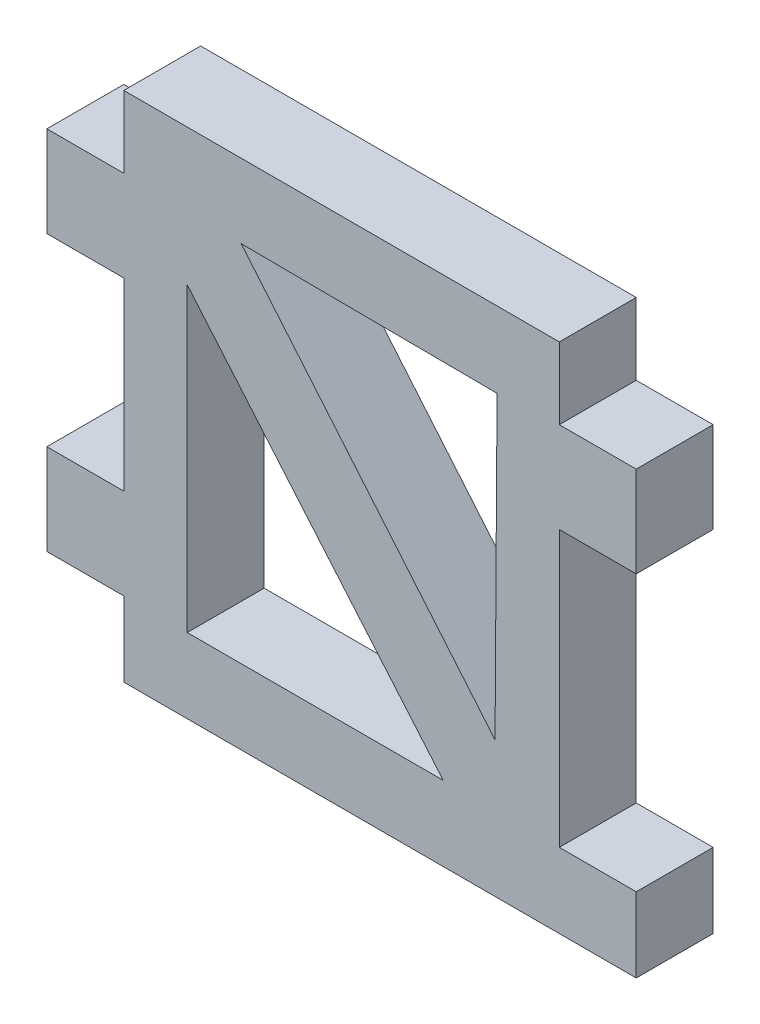
SolidWorks part; units mm, degrees
ref_plane "前视基准面" through (0, 0, 0) normal (0, 0, 1) x (1, 0, 0)
ref_plane "上视基准面" through (0, 0, 0) normal (0, 1, 0) x (1, 0, 0)
ref_plane "右视基准面" through (0, 0, 0) normal (1, 0, 0) x (0, 0, -1)
other "Configuration Table"
sketch "草图1" plane through (0, 0, 0) normal (0, 0, 1) x (1, 0, 0)
  line L0 (-28.32, 23.992) -> (-38.32, 23.992)
  line L1 (28.32, -33.32) -> (-28.32, -33.32)
  line L3 (28.32, 33.32) -> (-28.32, 33.32)
  line L4 (-28.32, -33.32) -> (-28.32, -23.608)
  line L5 (28.32, -33.32) -> (-28.32, 33.32) construction
  line L6 (28.32, 33.32) -> (-28.32, -33.32) construction
  line L7 (-38.32, 23.992) -> (-38.32, 12.192)
  line L8 (-38.32, 12.192) -> (-28.32, 12.192)
  line L9 (-28.32, -11.808) -> (-38.32, -11.808)
  line L10 (-38.32, -11.808) -> (-38.32, -23.608)
  line L11 (-38.32, -23.608) -> (-28.32, -23.608)
  line L12 (0, 33.32) -> (0, -33.32) construction
  line L13 (-28.32, 12.192) -> (-28.32, 23.992) construction
  line L14 (-28.32, 23.992) -> (-28.32, 33.32)
  line L15 (-28.32, -23.608) -> (-28.32, -11.808) construction
  line L16 (-28.32, -11.808) -> (-28.32, 12.192)
  line L23 (28.32, -33.32) -> (38.32, -33.32)
  line L24 (28.32, -23.608) -> (28.32, 12.192)
  line L25 (38.32, -33.32) -> (38.32, -23.608)
  line L27 (-20.0654, 15.5491) -> (13.2158, -23.608)
  line L28 (13.2158, -23.608) -> (-20.0654, -23.608)
  line L29 (-20.0654, -23.608) -> (-20.0654, 15.5491)
  line L30 (19.9616, -15.6821) -> (-13.0586, 23.6953)
  line L31 (-13.0586, 23.6953) -> (20.2218, 23.4742)
  line L32 (20.2218, 23.4742) -> (19.9616, -15.6821)
  line L33 (38.32, -23.608) -> (28.32, -23.608)
  line L34 (28.32, 12.192) -> (38.32, 12.192)
  line L35 (38.32, 12.192) -> (38.32, 23.992)
  line L36 (38.32, 23.992) -> (28.32, 23.992)
  line L37 (28.32, 12.192) -> (28.32, 23.992) construction
  line L38 (28.32, 23.992) -> (28.32, 33.32)
  line L39 (28.32, -33.32) -> (28.32, -23.608) construction
  point P0 (0, 0)
  point P32 (0, 0)
  dimension "D1" = 56.64
  dimension "D2" = 66.64
  dimension "D3" = 11.8
  dimension "D4" = 10
  dimension "D5" = 10
  dimension "D6" = 9.328
  dimension "D7" = 24
  dimension "D8" = 11.8
  dimension "D10" = 9.712
  dimension "D11" = 35.8
  dimension "D12" = 11.8
  dimension "D13" = 10
  dimension "D14" = 10
  dimension "D9" = 2
extrude "凸台-拉伸1" add sketch "草图1" along normal blind 10
